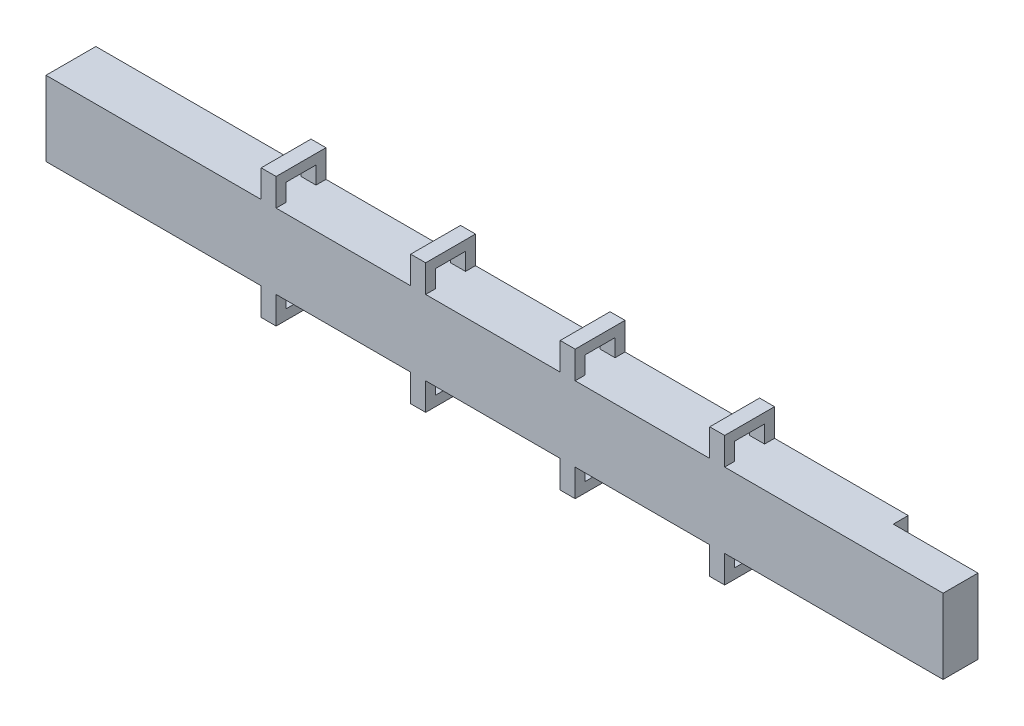
SolidWorks part; units mm, degrees
ref_plane "Front Plane" through (0, 0, 0) normal (0, 0, 1) x (1, 0, 0)
ref_plane "Top Plane" through (0, 0, 0) normal (0, 1, 0) x (1, 0, 0)
ref_plane "Right Plane" through (0, 0, 0) normal (1, 0, 0) x (0, 0, -1)
sketch "Sketch1" plane through (0, 0, 0) normal (0, 1, 0) x (1, 0, 0)
  line L1 (-90, -5) -> (90, -5)
  line L2 (-90, -5) -> (-90, 5)
  line L3 (-90, 5) -> (90, 5)
  line L4 (90, -5) -> (90, 5)
  line L5 (-90, -5) -> (90, 5) construction
  line L6 (-90, 5) -> (90, -5) construction
  point P0 (0, 0)
  dimension "D1" = 180
  dimension "D2" = 10
extrude "Boss-Extrude1" add sketch "Sketch1" along normal blind 15
sketch "Sketch2" plane through (0, 0, -5) normal (0, 0, -1) x (-1, 0, 0)
  line L0 (-90, 15) -> (90, 15) construction
  line L1 (-90, 0) -> (-73, 0)
  line L2 (-90, 0) -> (-90, 15)
  line L3 (-90, 15) -> (-73, 15)
  line L4 (-73, 0) -> (-73, 15)
  dimension "D1" = 17
extrude "Cut-Extrude1" cut sketch "Sketch2" against normal blind 3 contours L4 L3 L2 L1
sketch "Sketch3" plane through (0, 15, 0) normal (0, 1, 0) x (1, 0, 0)
  line L0 (73, 5) -> (-90, 5) construction
  line L1 (43.1736, -5) -> (46.1736, -5)
  line L2 (43.1736, -5) -> (43.1736, 5)
  line L3 (43.1736, 5) -> (46.1736, 5)
  line L4 (46.1736, -5) -> (46.1736, 5)
  line L5 (43.1736, -5) -> (46.1736, 5) construction
  line L6 (43.1736, 5) -> (46.1736, -5) construction
  point P0 (44.6736, 0)
  dimension "D1" = 3
extrude "Boss-Extrude2" add sketch "Sketch3" along normal blind 5.5 contours L2 L3 L4 L1
sketch "Sketch4" plane through (46.1736, 0, 0) normal (1, 0, 0) x (0, 0, -1)
  line L0 (-5, 15) -> (5, 15) construction
  line L1 (3, 18.5) -> (-3, 18.5)
  line L2 (3, 18.5) -> (3, 15)
  line L3 (3, 15) -> (-3, 15)
  line L4 (-3, 18.5) -> (-3, 15)
  line L5 (3, 18.5) -> (-3, 15) construction
  line L6 (3, 15) -> (-3, 18.5) construction
  line L7 (-5, 20.5) -> (5, 20.5) construction
  line L8 (-5, 20.5) -> (-5, 15) construction
  line L9 (5, 20.5) -> (5, 15) construction
  point P0 (0, 16.75)
  dimension "D1" = 2
  dimension "D2" = 2
  dimension "D3" = 2
extrude "Cut-Extrude2" cut sketch "Sketch4" against normal blind 7
pattern_linear "LPattern1" count 4 spacing 30 along (-1, 0, 0) of "Boss-Extrude2", "Cut-Extrude2"
ref_plane "Plane1" through (0, 7.5, 0) normal (0, -1, 0) x (-1, 0, 0)
mirror "Mirror1" about plane through (0, 7.5, 0) normal (0, -1, 0) of "LPattern1", "Boss-Extrude2", "Cut-Extrude2"
